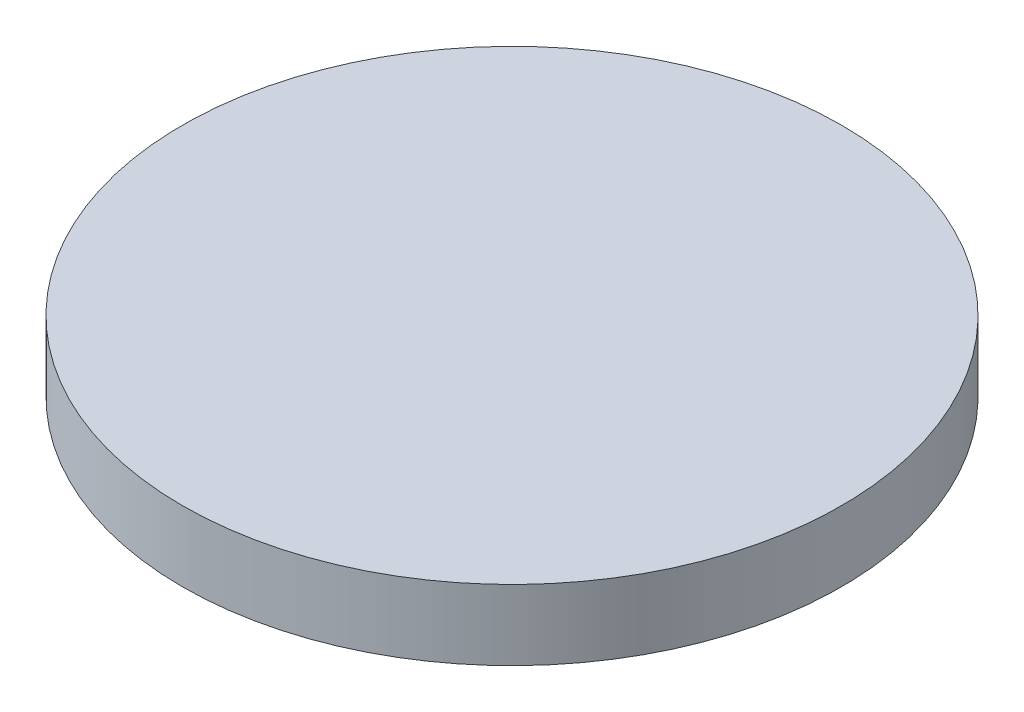
SolidWorks part; units mm, degrees
ref_plane "Plan de face" through (0, 0, 0) normal (0, 0, 1) x (1, 0, 0)
ref_plane "Plan de dessus" through (0, 0, 0) normal (0, 1, 0) x (1, 0, 0)
ref_plane "Plan de droite" through (0, 0, 0) normal (1, 0, 0) x (0, 0, -1)
sketch "Esquisse1" plane through (0, 0, 0) normal (0, 1, 0) x (1, 0, 0)
  circle A0 centre (0, 0) radius 7.5
extrude "Boss.-Extru.1" add sketch "Esquisse1" along normal blind 1.6 contours A0
